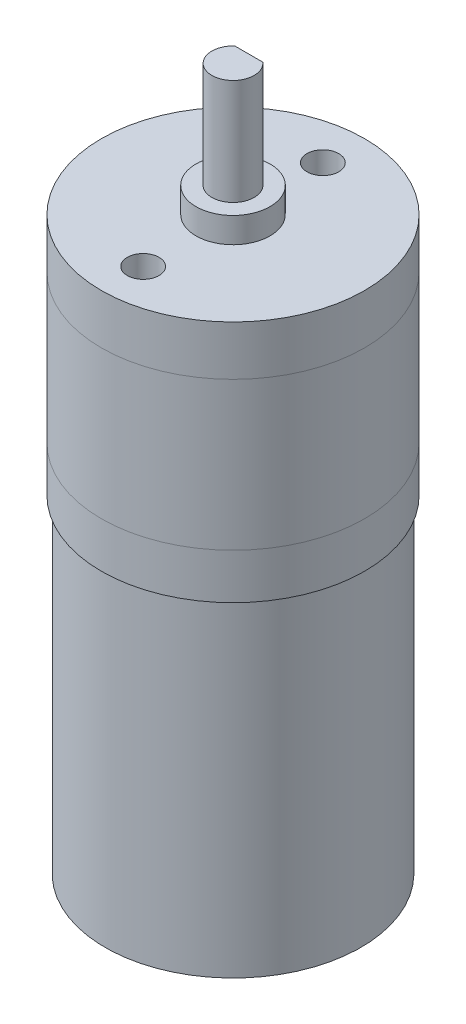
SolidWorks part; units mm, degrees
ref_plane "Спереди" through (0, 0, 0) normal (0, 0, 1) x (1, 0, 0)
ref_plane "Сверху" through (0, 0, 0) normal (0, 1, 0) x (1, 0, 0)
ref_plane "Справа" through (0, 0, 0) normal (1, 0, 0) x (0, 0, -1)
sketch "Эскиз2" plane through (0, 0, 0) normal (0, 1, 0) x (1, 0, 0)
  line L0 (-1.3229, 1.5) -> (1.3229, 1.5)
  circle A0 centre (0, 0) radius 2
  point P3 (0, -2)
  dimension "D1" = 4
  dimension "D2" = 3.5
extrude "Бобышка-Вытянуть1" add sketch "Эскиз2" against normal blind 8 contours L0 A0
sketch "Эскиз3" plane through (0, -8, 0) normal (0, -1, 0) x (-1, 0, 0)
  circle A0 centre (0, 0) radius 2
extrude "Бобышка-Вытянуть2" add sketch "Эскиз3" along normal blind 2
sketch "Эскиз4" plane through (0, -10, 0) normal (0, -1, 0) x (-1, 0, 0)
  circle A0 centre (0, 0) radius 3.5
  dimension "D1" = 7
extrude "Бобышка-Вытянуть3" add sketch "Эскиз4" along normal blind 2.4
sketch "Эскиз5" plane through (0, -12.4, 0) normal (0, -1, 0) x (-1, 0, 0)
  circle A0 centre (0, 0) radius 12.45
  dimension "D1" = 24.9
extrude "Бобышка-Вытянуть4" add sketch "Эскиз5" along normal blind 4.7
sketch "Эскиз6" plane through (0, -17.1, 0) normal (0, -1, 0) x (-1, 0, 0)
  circle A0 centre (0, 0) radius 12.4495
  dimension "D1" = 24.899
extrude "Бобышка-Вытянуть5" add sketch "Эскиз6" along normal blind 14
sketch "Эскиз7" plane through (0, -31.1, 0) normal (0, -1, 0) x (-1, 0, 0)
  circle A0 centre (0, 0) radius 12.45
  dimension "D1" = 24.9
extrude "Бобышка-Вытянуть6" add sketch "Эскиз7" along normal blind 4.3
sketch "Эскиз8" plane through (0, -35.4, 0) normal (0, -1, 0) x (-1, 0, 0)
  circle A0 centre (0, 0) radius 12.1
  dimension "D1" = 24.2
extrude "Бобышка-Вытянуть7" add sketch "Эскиз8" along normal blind 31
sketch "Эскиз9" plane through (0, -66.4, 0) normal (0, -1, 0) x (-1, 0, 0)
  circle A0 centre (0, 0) radius 11.6
  circle A1 centre (0, 0) radius 12.1 construction
  dimension "D1" = 0.5
extrude "Вырез-Вытянуть3" cut sketch "Эскиз9" against normal blind 1
sketch "Эскиз10" plane through (0, -65.4, 0) normal (0, -1, 0) x (-1, 0, 0)
  circle A0 centre (0, 0) radius 3
  dimension "D1" = 6
extrude "Бобышка-Вытянуть8" add sketch "Эскиз10" along normal blind 2
fillet "Скругление1" radius 1 1 edges at (0, -67.4, -3)
sketch "Эскиз11" plane through (0, -12.4, 0) normal (0, 1, 0) x (1, 0, 0)
  circle A0 centre (0, 8.5) radius 1.5
  circle A1 centre (0, -8.5) radius 1.5
  dimension "D1" = 3
  dimension "D2" = 3
  dimension "D3" = 8.5
  dimension "D4" = 8.5
  dimension "D5" = 0
  dimension "D6" = 0
extrude "Вырез-Вытянуть4" cut sketch "Эскиз11" against normal blind 7
